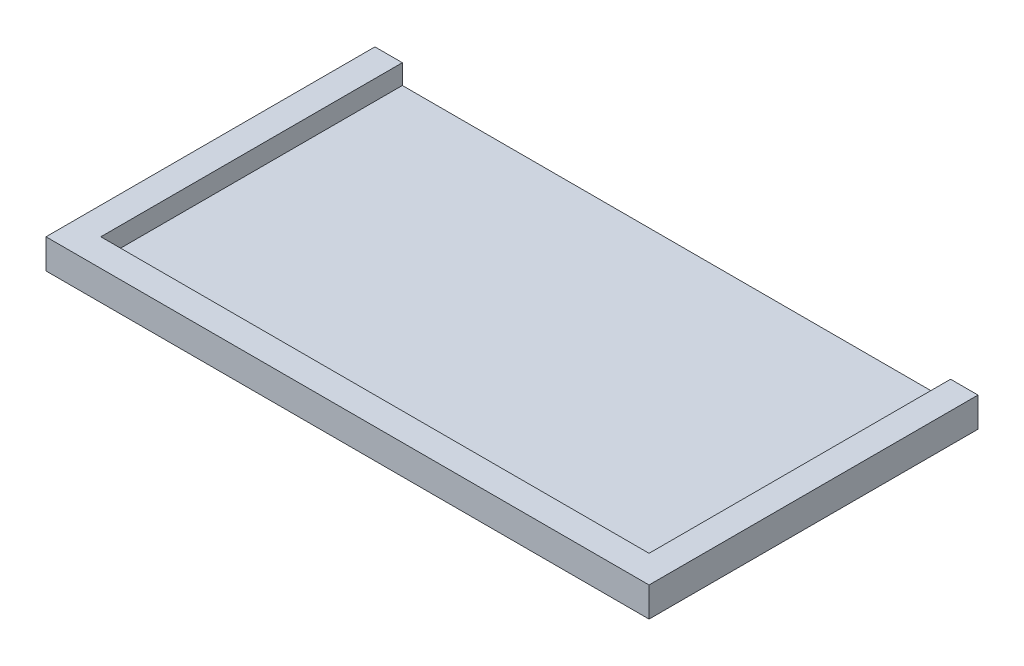
SolidWorks part; units mm, degrees
ref_plane "Front Plane" through (0, 0, 0) normal (0, 0, 1) x (1, 0, 0)
ref_plane "Top Plane" through (0, 0, 0) normal (0, 1, 0) x (1, 0, 0)
ref_plane "Right Plane" through (0, 0, 0) normal (1, 0, 0) x (0, 0, -1)
sketch "Sketch1" plane through (0, 0, 0) normal (0, 1, 0) x (1, 0, 0)
  line L1 (-27.5, -15) -> (27.5, -15)
  line L2 (-27.5, -15) -> (-27.5, 15)
  line L3 (-27.5, 15) -> (27.5, 15)
  line L4 (27.5, -15) -> (27.5, 15)
  line L5 (-27.5, -15) -> (27.5, 15) construction
  line L6 (-27.5, 15) -> (27.5, -15) construction
  point P0 (0, 0)
  dimension "D1" = 55
  dimension "D2" = 30
extrude "Boss-Extrude1" add sketch "Sketch1" along normal blind 0.9
sketch "Sketch2" plane through (0, 0.9, 0) normal (0, 1, 0) x (1, 0, 0)
  line L0 (27.5, -15) -> (27.5, 15) construction
  line L1 (-27.5, -15) -> (27.5, -15) construction
  line L2 (-27.5, 15) -> (-27.5, -15) construction
  line L3 (27.5, -15) -> (27.5, 15)
  line L4 (-27.5, -15) -> (27.5, -15)
  line L5 (-27.5, 15) -> (-27.5, -15)
  line L6 (-27.5, 15) -> (-25, 15)
  line L7 (27.5, 15) -> (-27.5, 15) construction
  line L8 (-25, 15) -> (-25, -12.5)
  line L9 (-25, -12.5) -> (25, -12.5)
  line L10 (25, -12.5) -> (25, 15)
  line L11 (25, 15) -> (27.5, 15)
  line L12 (25, -12.5) -> (25, -15) construction
  dimension "D1" = 2.5
extrude "Boss-Extrude2" add sketch "Sketch2" along normal blind 1.8
